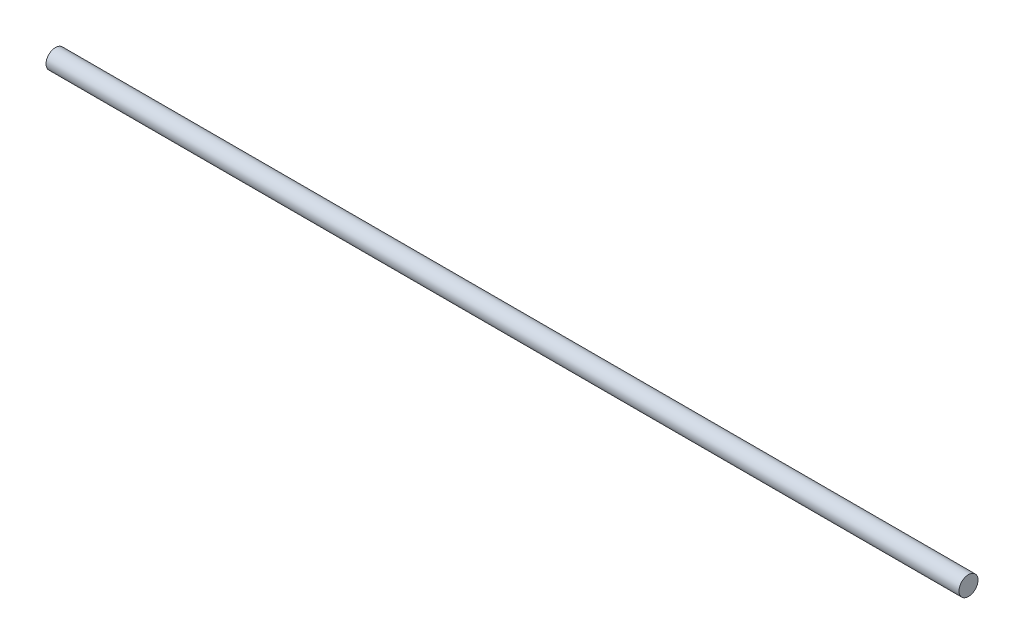
SolidWorks part; units mm, degrees
ref_plane "Front Plane" through (0, 0, 0) normal (0, 0, 1) x (1, 0, 0)
ref_plane "Top Plane" through (0, 0, 0) normal (0, 1, 0) x (1, 0, 0)
ref_plane "Right Plane" through (0, 0, 0) normal (1, 0, 0) x (0, 0, -1)
sketch "Sketch1" plane through (0, 0, 0) normal (1, 0, 0) x (0, 0, -1)
  circle A0 centre (0, 0) radius 6.35
  dimension "D1" = 12.7
extrude "Boss-Extrude1" add sketch "Sketch1" along normal mid plane 609.6
